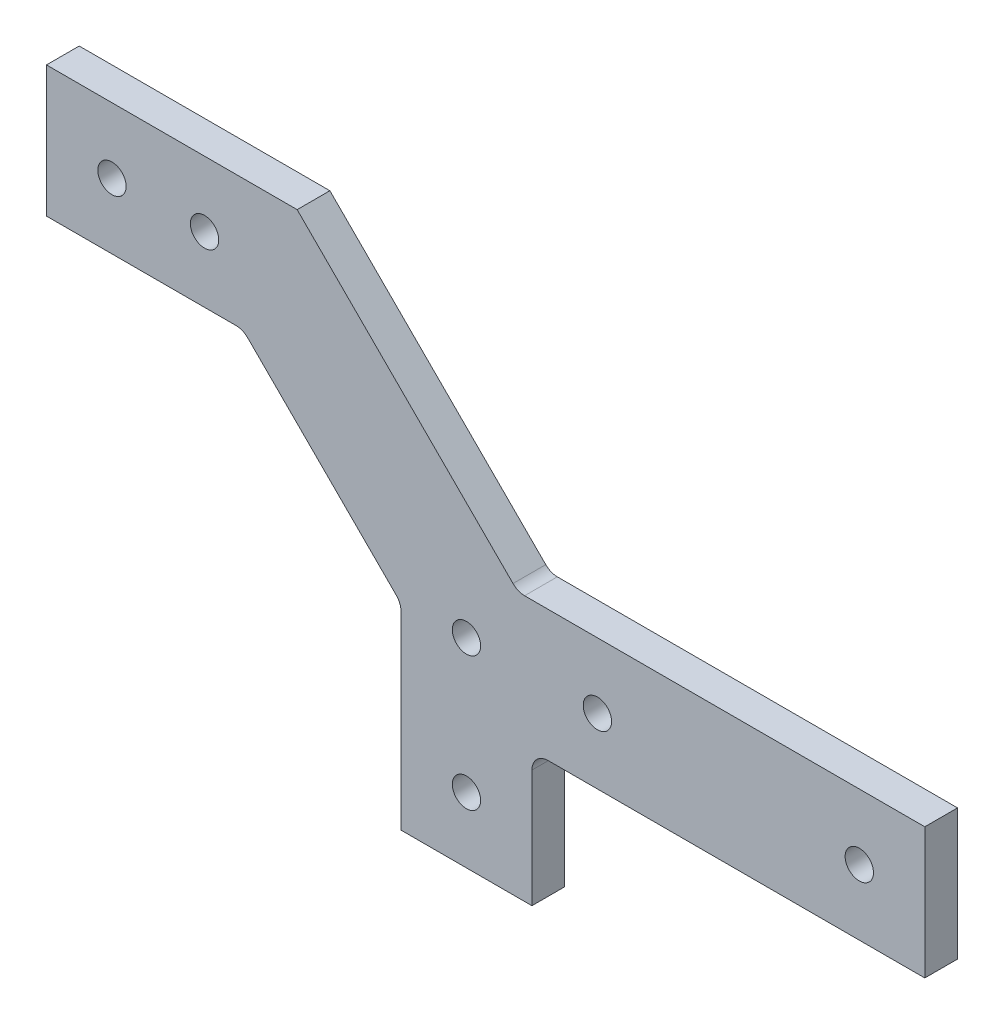
SolidWorks part; units mm, degrees
material "6061-T6 (SS)"
ref_plane "Front" through (0, 0, 0) normal (0, 0, 1) x (1, 0, 0)
ref_plane "Top" through (0, 0, 0) normal (0, 1, 0) x (1, 0, 0)
ref_plane "Right" through (0, 0, 0) normal (1, 0, 0) x (0, 0, -1)
sketch "Sketch4" plane through (-292.1, 0, 0) normal (0, 0, 1) x (1, 0, 0)
  line L0 (292.1, 63.5) -> (292.1, 0)
  line L1 (342.1, 0) -> (242.1, 0) construction
  line L2 (292.1, 63.5) -> (254, 101.6)
  line L4 (254, 101.6) -> (-254, 101.6)
  line L5 (292.1, 0) -> (-292.1, 0) construction
  line L6 (-254, 101.6) -> (-292.1, 63.5)
  line L7 (-292.1, 63.5) -> (-292.1, -25.4)
  dimension "D1" = 90
sketch "Sketch1" plane through (0, 0, 0) normal (0, 0, 1) x (1, 0, 0)
  line L0 (-12.7, 46.1) -> (-12.7, 58.2395)
  line L1 (12.7, 71.5) -> (88.9, 71.5)
  line L2 (88.9, 71.5) -> (88.9, 46.1)
  line L3 (88.9, 46.1) -> (12.7, 46.1)
  line L6 (-12.7, 58.2395) -> (-43.3605, 88.9)
  line L7 (-43.3605, 88.9) -> (-81.4605, 88.9)
  line L8 (-81.4605, 88.9) -> (-81.4605, 114.3)
  line L9 (-81.4605, 114.3) -> (-32.8395, 114.3)
  line L10 (-32.8395, 114.3) -> (9.9605, 71.5)
  line L11 (9.9605, 71.5) -> (12.7, 71.5)
  line L12 (-12.7, 46.1) -> (-12.7, 0) construction
  line L13 (0, 63.5) -> (-38.1, 101.6) construction
  line L14 (-38.1, 101.6) -> (-546.1, 101.6) construction
  line L15 (12.7, 71.5) -> (-12.7, 71.5) construction
  line L16 (-12.7, 71.5) -> (-12.7, 58.2395) construction
  line L17 (12.7, 46.1) -> (12.7, 20.1395)
  line L18 (12.7, 20.1395) -> (-12.7, 20.1395)
  line L19 (-12.7, 20.1395) -> (-12.7, 46.1)
  line L20 (12.7, 46.1) -> (-12.7, 46.1) construction
  line L21 (12.7, 71.5) -> (12.7, 46.1) construction
  line L22 (0, 0) -> (-584.2, 0) construction
  line L23 (0, 20.1395) -> (0, 0) construction
  dimension "D1" = 46.1
  dimension "D2" = 25.4
  dimension "D3" = 38.1
  dimension "D4" = 101.6
  dimension "D5" = 12.7
  dimension "D6" = 12.7
  dimension "D7" = 12.7
  dimension "D8" = 12.7
  dimension "D9" = 38.1
  dimension "D10" = 25.4
extrude "Boss-Extrude1" add sketch "Sketch1" along normal blind 6.35
fillet "Fillet1" radius 3.175 4 edges at (-43.3605, 88.9, 3.175) (-12.7, 58.2395, 3.175) (12.7, 46.1, 3.175) (9.9605, 71.5, 3.175)
hole_wizard "M5 Clearance Hole1" positions "Sketch2" profile "Sketch3" hole size "M5" standard "ANSI Metric"
sketch "Sketch2" plane through (0, 0, 6.35) normal (0, 0, 1) x (1, 0, 0)
  line L5 (88.9, 71.5) -> (76.2, 58.8) construction
  line L6 (76.2, 58.8) -> (88.9, 46.1) construction
  line L8 (76.2, 58.8) -> (25.4, 58.8) construction
  line L12 (25.4, 58.8) -> (0, 58.8) construction
  line L14 (-81.4605, 114.3) -> (-68.7605, 101.6) construction
  line L15 (-68.7605, 101.6) -> (-81.4605, 88.9) construction
  line L17 (-68.7605, 101.6) -> (-50.8, 101.6) construction
  line L22 (12.7, 20.1395) -> (0, 32.8395) construction
  line L23 (0, 32.8395) -> (-12.7, 20.1395) construction
  line L25 (0, 32.8395) -> (0, 58.8) construction
  point P0 (0, 58.8)
  point P4 (25.4, 58.8)
  point P6 (76.2, 58.8)
  point P48 (-50.8, 101.6)
  point P50 (-68.7605, 101.6)
  point P87 (0, 32.8395)
  dimension "D1" = 50.8
  dimension "D4" = 12.7
sketch "Sketch3" plane through (0, 58.8, 6.35) normal (1, 0, 0) x (0, -1, 0)
  line L0 (0, 0) -> (0, 20.4024)
  line L1 (0, 20.4024) -> (2.75, 18.75)
  line L2 (2.75, 18.75) -> (2.75, 0)
  line L5 (2.75, 0) -> (0, 0)
  line L10 (0, 20.4024) -> (-2.75, 18.75) construction
  line L11 (0, -6.35) -> (0, 107.95) construction
  dimension "Hole Dia." = 5.5
  dimension "Hole Depth" = 18.75
  dimension "Drill Angle" = 118
